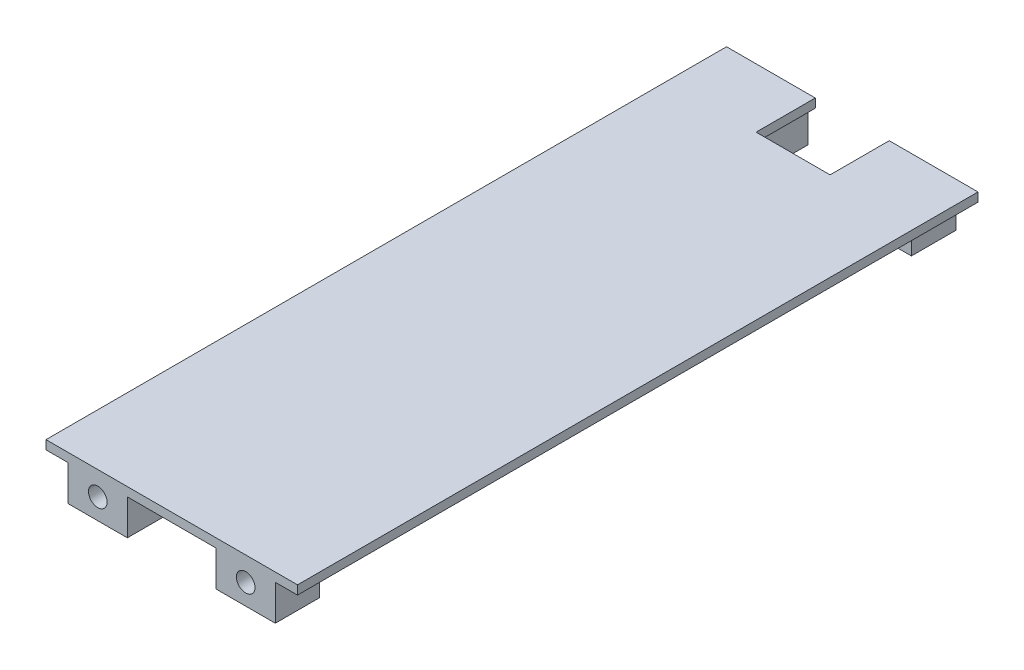
SolidWorks part; units mm, degrees
ref_plane "Front Plane" through (0, 0, 0) normal (0, 0, 1) x (1, 0, 0)
ref_plane "Top Plane" through (0, 0, 0) normal (0, 1, 0) x (1, 0, 0)
ref_plane "Right Plane" through (0, 0, 0) normal (1, 0, 0) x (0, 0, -1)
sketch "Sketch1" plane through (0, 0, 0) normal (0, 0, 1) x (1, 0, 0)
  line L0 (-42.5, 8) -> (42.5, 8)
  line L1 (-42.5, 5) -> (42.5, 5)
  line L2 (-42.5, 8) -> (-42.5, 5)
  line L3 (42.5, 8) -> (42.5, 5)
  line L4 (-35, 5) -> (-35, -7)
  line L5 (-35, -7) -> (-15, -7)
  line L6 (-15, -7) -> (-15, 5)
  line L7 (15, 5) -> (15, -7)
  line L8 (15, -7) -> (35, -7)
  line L9 (35, -7) -> (35, 5)
  circle A0 centre (0, 0) radius 47.6 construction
  circle A1 centre (-25, 0) radius 3.15
  circle A2 centre (25, 0) radius 3.15
  dimension "D1" = 95.2
  dimension "D2" = 6.3
  dimension "D3" = 6.3
  dimension "D4" = 25
  dimension "D5" = 25
  dimension "D6" = 8
  dimension "D8" = 12
  dimension "D9" = 20
  dimension "D10" = 10
  dimension "D11" = 20
  dimension "D12" = 12
  dimension "D13" = 10
  dimension "D14" = 85
  dimension "D15" = 42.5
  dimension "D7" = 3
extrude "Boss-Extrude1" add sketch "Sketch1" along normal blind 230 contours L5 L6 L1 L4 A1 | L8 L9 L1 L7 A2 | L3 L0 L2 L1
sketch "Sketch2" plane through (-35, 0, 0) normal (-1, 0, 0) x (0, 0, 1)
  line L0 (230, 5) -> (0, 5) construction
  line L1 (215, -10) -> (15, -10)
  line L2 (215, -10) -> (215, 5)
  line L3 (215, 5) -> (15, 5)
  line L4 (15, -10) -> (15, 5)
  line L5 (215, -10) -> (15, 5) construction
  line L6 (215, 5) -> (15, -10) construction
  line L7 (0, 5) -> (0, -7) construction
  line L8 (230, 5) -> (230, -7) construction
  point P0 (115, -2.5)
  dimension "D1" = 15
  dimension "D2" = 15
  dimension "D3" = 15
extrude "Cut-Extrude1" cut sketch "Sketch2" against normal blind 210
sketch "Sketch3" plane through (0, 5, 0) normal (0, -1, 0) x (1, 0, 0)
  line L0 (-15, 0) -> (15, 0) construction
  line L1 (18.5, 39.5) -> (-18.5, 39.5)
  line L2 (18.5, 39.5) -> (18.5, 170.5)
  line L3 (18.5, 170.5) -> (-18.5, 170.5)
  line L4 (-18.5, 39.5) -> (-18.5, 170.5)
  line L5 (18.5, 39.5) -> (-18.5, 170.5) construction
  line L6 (18.5, 170.5) -> (-18.5, 39.5) construction
  line L7 (-21.8, 36.2) -> (-21.8, 173.8)
  line L8 (21.8, 173.8) -> (-21.8, 173.8)
  line L9 (21.8, 36.2) -> (21.8, 173.8)
  line L10 (21.8, 36.2) -> (-21.8, 36.2)
  point P0 (0, 105)
  dimension "D1" = 37
  dimension "D2" = 131
  dimension "D3" = 105
  dimension "D4" = 3.3
extrude "Boss-Extrude2" add sketch "Sketch3" along normal blind 12
sketch "Sketch4" plane through (0, 0, 36.2) normal (0, 0, -1) x (-1, 0, 0)
  line L0 (0, 0) -> (-7.5, 0)
  line L1 (-7.5, 0) -> (-7.5, -8)
  line L2 (-7.5, -8) -> (7.5, -8)
  line L3 (7.5, -8) -> (7.5, 0)
  line L4 (7.5, 0) -> (0, 0)
  dimension "D1" = 15
  dimension "D2" = 7.5
  dimension "D3" = 8
extrude "Cut-Extrude2" cut sketch "Sketch4" against normal through all
sketch "Sketch6" plane through (0, 0, 36.2) normal (0, 0, -1) x (-1, 0, 0)
  line L0 (7.5, 0) -> (-7.5, 0) construction
  circle A0 centre (-12, -4) radius 2.5
  circle A1 centre (12, -4) radius 2.5
  point P7 (0, 0)
  dimension "D3" = 5
  dimension "D4" = 5
  dimension "D1" = 24
  dimension "D2" = 12
  dimension "D5" = 4
  dimension "D6" = 4
extrude "Cut-Extrude3" cut sketch "Sketch6" against normal blind 150
sketch "Sketch7" plane through (0, 8, 0) normal (0, 1, 0) x (1, 0, 0)
  line L1 (12.5, -20) -> (-12.5, -20)
  line L2 (12.5, -20) -> (12.5, 20)
  line L3 (12.5, 20) -> (-12.5, 20)
  line L4 (-12.5, -20) -> (-12.5, 20)
  line L5 (12.5, -20) -> (-12.5, 20) construction
  line L6 (12.5, 20) -> (-12.5, -20) construction
  point P0 (0, 0)
  point P6 (12.5, 0)
  dimension "D1" = 40
  dimension "D2" = 25
extrude "Cut-Extrude4" cut sketch "Sketch7" against normal blind 150
equation "\"D2@Sketch4\"=\"D1@Sketch4\"/2"
equation "\"D2@Sketch6\"=\"D1@Sketch6\"/2"
